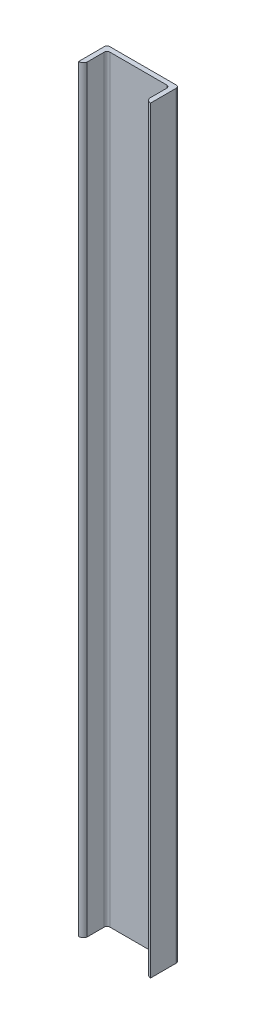
SolidWorks part; units mm, degrees
ref_plane "Front Plane" through (0, 0, 0) normal (0, 0, 1) x (1, 0, 0)
ref_plane "Top Plane" through (0, 0, 0) normal (0, 1, 0) x (1, 0, 0)
ref_plane "Right Plane" through (0, 0, 0) normal (1, 0, 0) x (0, 0, -1)
sketch "Sketch2" plane through (0, 0, 0) normal (0, 1, 0) x (1, 0, 0)
  line L2 (38, 12.1871) -> (38, -17.8129)
  line L3 (33, -13.8327) -> (33, 7.1871)
  line L6 (0, -1000) -> (0, 49000) construction
  line L7 (33, 7.1871) -> (-33, 7.1871)
  line L8 (38, 12.1871) -> (-38, 12.1871)
  line L9 (-33, -13.8327) -> (-33, 7.1871)
  line L10 (-38, 12.1871) -> (-38, -17.8129)
  arc A0 (38, -17.8129) -> (33, -13.8327) centre (38, -12.6822) cw
  arc A2 (-38, -17.8129) -> (-33, -13.8327) centre (-38, -12.6822) ccw
  point P14 (0, 12.1871)
  point P15 (0, 7.1871)
  dimension "D2" = 5.1307
  dimension "D1" = 76
  dimension "D3" = 5
  dimension "D4" = 30
  dimension "D5" = 7.1871
  dimension "D6" = 12.1871
extrude "Boss-Extrude1" add sketch "Sketch2" along normal blind 800
fillet "Fillet1" radius 3 4 edges at (-33, 400, -7.1871) (33, 400, -7.1871) (38, 400, -12.1871) (-38, 400, -12.1871)
equation "\"CarBeamWidth\"=700.0"
equation "\"D1@Boss-Extrude1\"=\"CarBeamWidth\"+100"
equation "\"WheelWidth\"=650.0"
equation "\"Wheel_FrontBoxDistance\"=1390.0"
equation "\"MetalSheet_3mm_length\"=5030.0"
equation "\"MetalSheet_3mm_width\"=1923.0"
equation "\"MetalSheet_3mm_FloorCut_L_length\"=1764.0"
equation "\"MetalSheet_3mm_FloorCut_L_disdance\"=1665.0"
equation "\"MetalSheet_3mm_FloorCut_R_length\"=1764.0"
equation "\"MetalSheet_3mm_FloorCut_R_disdance\"=1665.0"
equation "\"indoorHeight\"=1940.0"
equation "\"indoorHeight_para\"=25.0"
equation "\"haveDoor_R\"=1"
equation "\"side_door_bottom_R_3mm_length\"=1934.0"
equation "\"side_door_bottom_R_3mm_toFrontDistance\"=1583.0"
equation "\"1Bar_Side_RF_3mm_length\"=1493.0"
equation "\"1Bar_Side_RB_3mm_length\"=1493.0"
equation "\"DoorSeparator_RF_3mm_withHinge_toFrontDistance\"=1673.0"
equation "\"DoorSeparator_RF_3mm_withHinge_exist\"=1"
equation "\"DoorSeparator_RB_3mm_withHinge_toFrontDistance\"=3427.0"
equation "\"DoorSeparator_RB_3mm_withHinge_exist\"=1"
equation "\"Door_R1_L_open_Single_toFrontDistance\"=2547.5"
equation "\"Door_R1_L_open_Single_exist\"=1"
equation "\"door_base_long7_R1_L_open_Single_height\"=1890.0"
equation "\"door_base_short7_R1_L_open_Single_height\"=1890.0"
equation "\"door_base_short7_R1_L_open_Single_width\"=864"
equation "\"Door_R1_R_open_Single_toFrontDistance\"=3422.0"
equation "\"Door_R1_R_open_Single_exist\"=1"
equation "\"door_base_long7_R1_R_open_Single_height\"=1890.0"
equation "\"door_base_short7_R1_R_open_Single_height\"=1890.0"
equation "\"door_base_short7_R1_R_open_Single_width\"=864"
equation "\"x\"=66.0"
equation "\"da\"=62.0"
equation "\"SquareTube_length\"=1923.0"
equation "\"channelSteel_length\"=5030.0"
equation "\"SquareTube_inFront_AvgDistance\"=285.0"
equation "\"SquareTube_inFront_TotalCount\"=5"
equation "\"SquareTube_inFront1_cutDepth50_R\"=0.5"
equation "\"SquareTube_inFront1_cutDepth50_L\"=0.5"
equation "\"SquareTube_inFront2_cutDepth50_R\"=0.5"
equation "\"SquareTube_inFront2_cutDepth50_L\"=0.5"
equation "\"SquareTube_inFront3_cutDepth50_R\"=0.5"
equation "\"SquareTube_inFront3_cutDepth50_L\"=0.5"
equation "\"SquareTube_inFront4_cutDepth50_R\"=0.5"
equation "\"SquareTube_inFront4_cutDepth50_L\"=0.5"
equation "\"SquareTube_inFront5_cutDepth50_R\"=50"
equation "\"SquareTube_inFront5_cutDepth50_L\"=50"
equation "\"SquareTube_inFront6_cutDepth50_R\"=50"
equation "\"SquareTube_inFront6_cutDepth50_L\"=50"
equation "\"SquareTube_inFront7_cutDepth50_R\"=50"
equation "\"SquareTube_inFront7_cutDepth50_L\"=50"
equation "\"SquareTube_inFront8_cutDepth50_R\"=50"
equation "\"SquareTube_inFront8_cutDepth50_L\"=50"
equation "\"SquareTube_inFront9_cutDepth50_R\"=50"
equation "\"SquareTube_inFront9_cutDepth50_L\"=50"
equation "\"SquareTube_inFront10_cutDepth50_R\"=50"
equation "\"SquareTube_inFront10_cutDepth50_L\"=50"
equation "\"SquareTube_inFront11_cutDepth50_R\"=50"
equation "\"SquareTube_inFront11_cutDepth50_L\"=50"
equation "\"SquareTube_inFront12_cutDepth50_R\"=50"
equation "\"SquareTube_inFront12_cutDepth50_L\"=50"
equation "\"SquareTube_inFront13_cutDepth50_R\"=50"
equation "\"SquareTube_inFront13_cutDepth50_L\"=50"
equation "\"SquareTube_inFront14_cutDepth50_R\"=50"
equation "\"SquareTube_inFront14_cutDepth50_L\"=50"
equation "\"SquareTube_inBack_AvgDistance\"=333.125"
equation "\"SquareTube_inBack_TotalCount\"=9"
equation "\"SquareTube_inBack1_cutDepth50_R\"=50"
equation "\"SquareTube_inBack1_cutDepth50_L\"=50"
equation "\"SquareTube_inBack2_cutDepth50_R\"=50"
equation "\"SquareTube_inBack2_cutDepth50_L\"=50"
equation "\"SquareTube_inBack3_cutDepth50_R\"=50"
equation "\"SquareTube_inBack3_cutDepth50_L\"=50"
equation "\"SquareTube_inBack4_cutDepth50_R\"=50"
equation "\"SquareTube_inBack4_cutDepth50_L\"=50"
equation "\"SquareTube_inBack5_cutDepth50_R\"=50"
equation "\"SquareTube_inBack5_cutDepth50_L\"=50"
equation "\"SquareTube_inBack6_cutDepth50_R\"=0.5"
equation "\"SquareTube_inBack6_cutDepth50_L\"=0.5"
equation "\"SquareTube_inBack7_cutDepth50_R\"=0.5"
equation "\"SquareTube_inBack7_cutDepth50_L\"=0.5"
equation "\"SquareTube_inBack8_cutDepth50_R\"=0.5"
equation "\"SquareTube_inBack8_cutDepth50_L\"=0.5"
